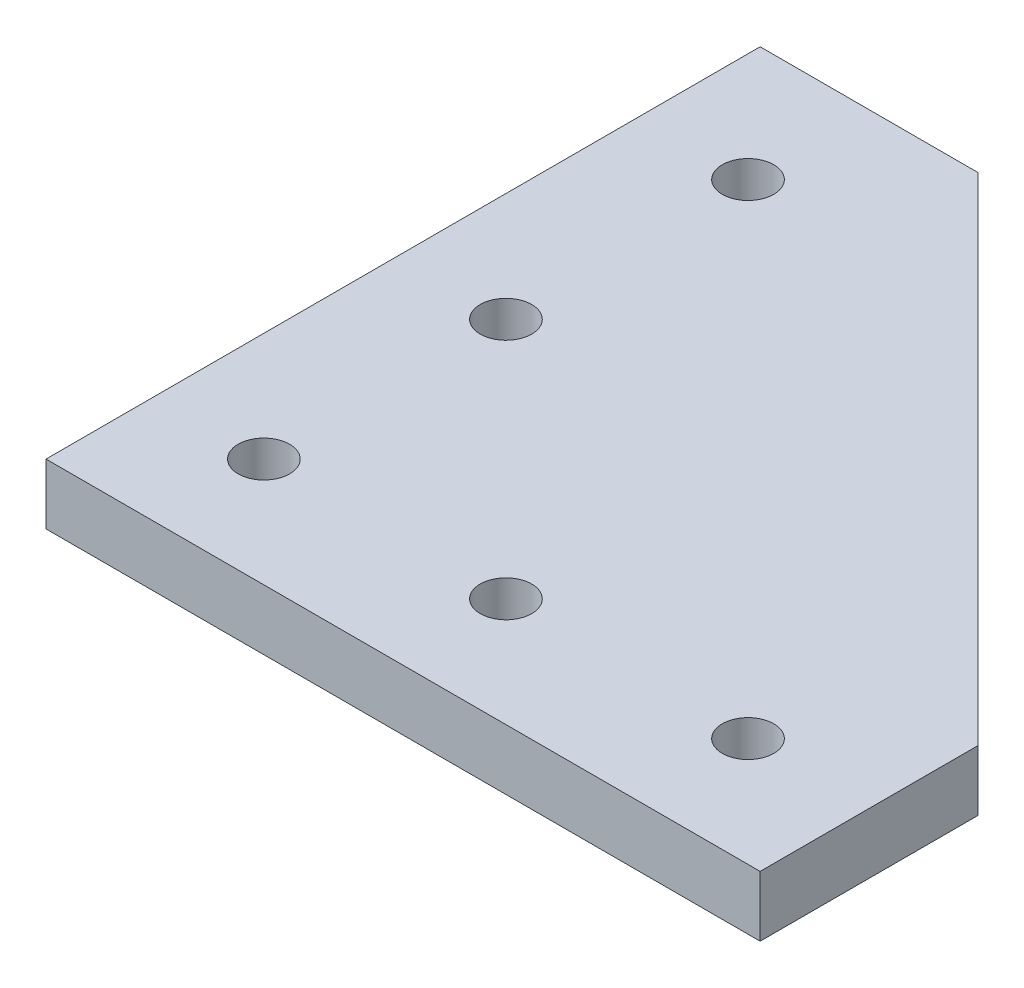
SolidWorks part; units mm, degrees
ref_plane "Front Plane" through (0, 0, 0) normal (0, 0, 1) x (1, 0, 0)
ref_plane "Top Plane" through (0, 0, 0) normal (0, 1, 0) x (1, 0, 0)
ref_plane "Right Plane" through (0, 0, 0) normal (1, 0, 0) x (0, 0, -1)
sketch "Sketch1" plane through (0, 0, 0) normal (0, 1, 0) x (1, 0, 0)
  line L0 (59, -59) -> (67.9606, -59) construction
  line L1 (-59, -59) -> (59, -59)
  line L2 (-59, -59) -> (-59, 59)
  line L3 (-59, 59) -> (-23, 59)
  line L4 (59, -59) -> (59, -23)
  line L5 (-59, -59) -> (18, 18) construction
  line L6 (-59, 59) -> (59, -59) construction
  line L7 (67.9606, -59) -> (67.9606, -23) construction
  line L8 (67.9606, -23) -> (59, -23) construction
  line L9 (-59, 59) -> (-59, 70.6371) construction
  line L10 (-59, 70.6371) -> (-23, 70.6371) construction
  line L11 (-23, 70.6371) -> (-23, 59) construction
  line L12 (-23, 59) -> (59, -23)
  circle A0 centre (-41, -41) radius 4.25
  circle A1 centre (-1, -41) radius 4.25
  circle A2 centre (39, -41) radius 4.25
  circle A3 centre (-41, -1) radius 4.25
  circle A4 centre (-41, 39) radius 4.25
  point P0 (0, 0)
  dimension "D6" = 18
  dimension "D7" = 8.5
  dimension "D8" = 8.5
  dimension "D9" = 8.5
  dimension "D10" = 40
  dimension "D13" = 8.5
  dimension "D15" = 8.5
  dimension "D1" = 118
  dimension "D2" = 118
  dimension "D3" = 36
  dimension "D4" = 36
  dimension "D5" = 18
  dimension "D11" = 40
  dimension "D12" = 40
  dimension "D14" = 40
extrude "Boss-Extrude1" add sketch "Sketch1" along normal blind 10
